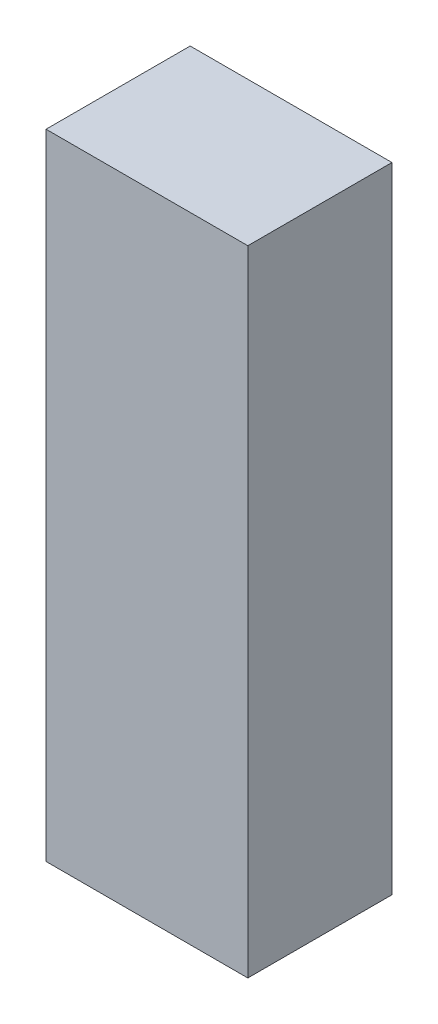
SolidWorks part; units mm, degrees
ref_plane "Front Plane" through (0, 0, 0) normal (1, 0, 0) x (0, 1, 0)
ref_plane "Top Plane" through (0, 0, 0) normal (0, 0, 1) x (0, 1, 0)
ref_plane "Right Plane" through (0, 0, 0) normal (0, 1, 0) x (-1, 0, 0)
sketch "Sketch1" plane through (0, 0, 0) normal (0, 0, 1) x (0, 1, 0)
  line L1 (0, 0) -> (110, 0)
  line L2 (0, 0) -> (0, -35)
  line L3 (0, -35) -> (110, -35)
  line L4 (110, 0) -> (110, -35)
  dimension "D1" = 35
  dimension "D2" = 110
extrude "Boss-Extrude1" add sketch "Sketch1" along normal blind 25
